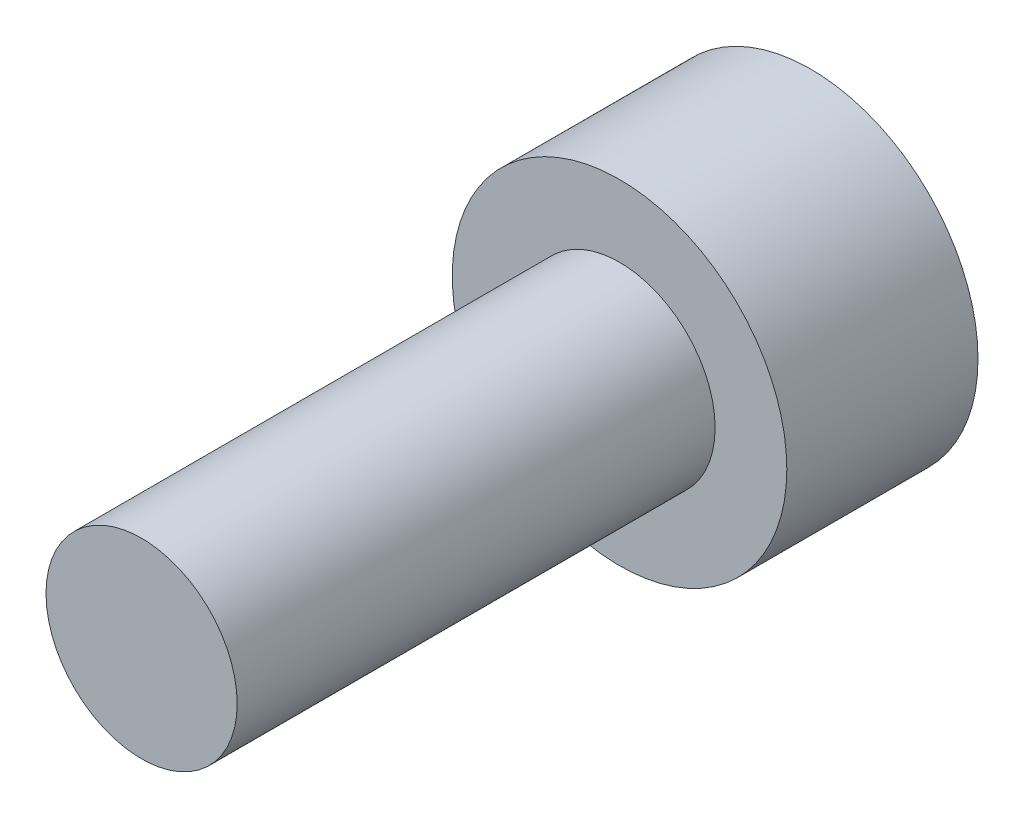
SolidWorks part; units mm, degrees
ref_plane "正面" through (0, 0, 0) normal (0, 0, 1) x (1, 0, 0)
ref_plane "平面" through (0, 0, 0) normal (0, 1, 0) x (1, 0, 0)
ref_plane "右側面" through (0, 0, 0) normal (1, 0, 0) x (0, 0, -1)
sketch "ｽｹｯﾁ1" plane through (0, 0, 0) normal (0, 0, 1) x (1, 0, 0)
  circle A0 centre (0, 0) radius 3.5
  dimension "D1" = 7
extrude "ﾎﾞｽ - 押し出し1" add sketch "ｽｹｯﾁ1" along normal blind 4
sketch "ｽｹｯﾁ2" plane through (0, 0, 4) normal (0, 0, 1) x (1, 0, 0)
  circle A0 centre (0, 0) radius 2
  dimension "D1" = 4
extrude "ﾎﾞｽ - 押し出し2" add sketch "ｽｹｯﾁ2" along normal blind 10
cosmetic thread "ねじ山1" parameters "D2"=3
sketch "ｽｹｯﾁ3" plane through (0, 0, 0) normal (0, 0, -1) x (-1, 0, 0)
  line L1 (1.7041, -0.9463) -> (1.6716, 1.0026)
  line L2 (1.6716, 1.0026) -> (-0.0325, 1.949)
  line L3 (-0.0325, 1.949) -> (-1.7041, 0.9463)
  line L4 (-1.7041, 0.9463) -> (-1.6716, -1.0026)
  line L5 (-1.6716, -1.0026) -> (0.0325, -1.949)
  line L6 (0.0325, -1.949) -> (1.7041, -0.9463)
  circle A0 centre (0, 0) radius 1.6881 construction
extrude "ｶｯﾄ - 押し出し1" cut sketch "ｽｹｯﾁ3" against normal blind 2
